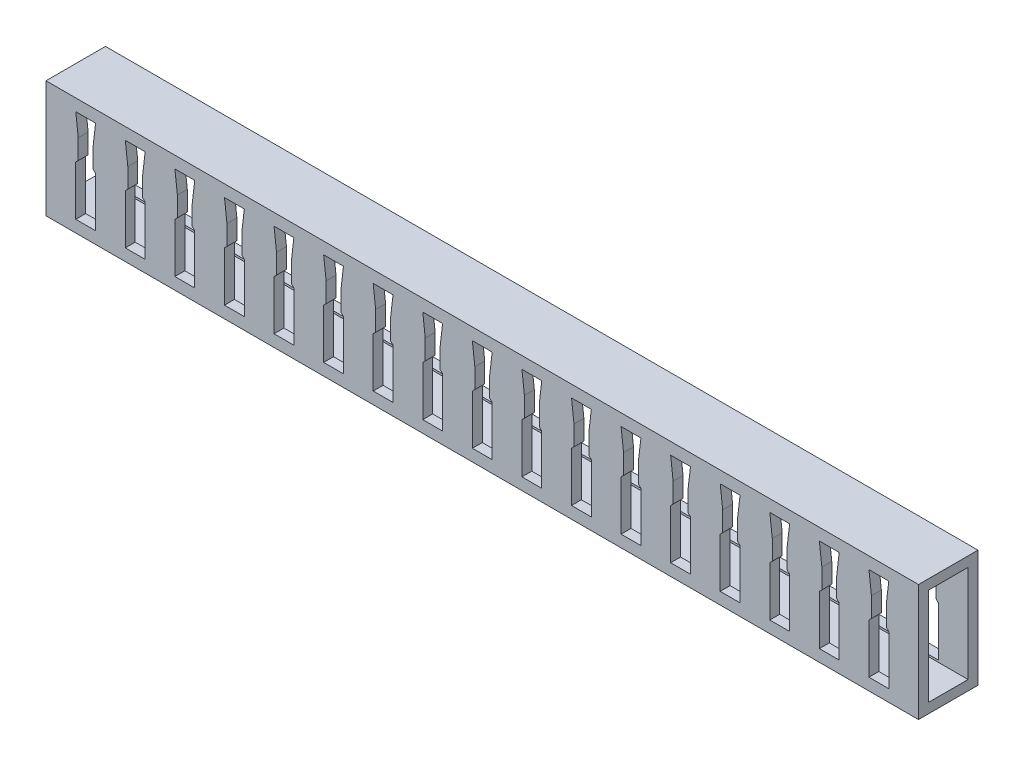
SolidWorks part; units mm, degrees
ref_plane "Front Plane" through (0, 0, 0) normal (0, 0, 1) x (1, 0, 0)
ref_plane "Top Plane" through (0, 0, 0) normal (0, 1, 0) x (1, 0, 0)
ref_plane "Right Plane" through (0, 0, 0) normal (1, 0, 0) x (0, 0, -1)
sketch "Sketch2" plane through (0, 0, 0) normal (1, 0, 0) x (0, 0, -1)
  line L1 (0, 0) -> (15.24, 0)
  line L2 (0, 0) -> (0, 29.972)
  line L3 (0, 29.972) -> (15.24, 29.972)
  line L4 (15.24, 0) -> (15.24, 29.972)
  dimension "D1" = 15.24
  dimension "D2" = 29.972
extrude "Boss-Extrude1" add sketch "Sketch2" along normal blind 223.52
sketch "Sketch3" plane through (223.52, 0, 0) normal (1, 0, 0) x (0, 0, -1)
  line L8 (2.54, 27.432) -> (2.54, 2.54)
  line L9 (2.54, 2.54) -> (12.7, 2.54)
  line L10 (12.7, 2.54) -> (12.7, 27.432)
  line L11 (12.7, 27.432) -> (2.54, 27.432)
  line L12 (2.54, 27.432) -> (2.54, 2.54)
  line L13 (2.54, 2.54) -> (12.7, 2.54)
  line L14 (12.7, 2.54) -> (12.7, 27.432)
  line L15 (12.7, 27.432) -> (2.54, 27.432)
  dimension "D1" = 2.54
extrude "Cut-Extrude1" cut sketch "Sketch3" against normal blind 419.1
sketch "Sketch4" plane through (0, 0, 0) normal (0, 0, 1) x (1, 0, 0)
  line L0 (7.62, 3.048) -> (7.62, 15.748)
  line L1 (7.62, 15.748) -> (8.255, 16.383)
  line L2 (8.255, 16.383) -> (8.255, 21.463)
  line L3 (8.255, 21.463) -> (7.62, 26.924)
  line L4 (7.62, 26.924) -> (12.7, 26.924)
  line L5 (12.7, 26.924) -> (12.065, 21.463)
  line L6 (12.065, 21.463) -> (12.065, 16.383)
  line L7 (12.065, 16.383) -> (12.7, 15.748)
  line L8 (12.7, 15.748) -> (12.7, 3.048)
  line L9 (12.7, 3.048) -> (7.62, 3.048)
  line L10 (223.52, 29.972) -> (0, 29.972) construction
  line L11 (223.52, 0) -> (0, 0) construction
  line L12 (0, 29.972) -> (0, 0) construction
  line L13 (25.4, 3.048) -> (20.32, 3.048)
  line L14 (20.32, 3.048) -> (20.32, 15.748)
  line L15 (20.32, 15.748) -> (20.955, 16.383)
  line L16 (20.955, 16.383) -> (20.955, 21.463)
  line L17 (20.955, 21.463) -> (20.32, 26.924)
  line L18 (20.32, 26.924) -> (25.4, 26.924)
  line L19 (25.4, 26.924) -> (24.765, 21.463)
  line L20 (24.765, 21.463) -> (24.765, 16.383)
  line L21 (24.765, 16.383) -> (25.4, 15.748)
  line L22 (25.4, 15.748) -> (25.4, 3.048)
  line L23 (38.1, 3.048) -> (33.02, 3.048)
  line L24 (33.02, 3.048) -> (33.02, 15.748)
  line L25 (33.02, 15.748) -> (33.655, 16.383)
  line L26 (33.655, 16.383) -> (33.655, 21.463)
  line L27 (33.655, 21.463) -> (33.02, 26.924)
  line L28 (33.02, 26.924) -> (38.1, 26.924)
  line L29 (38.1, 26.924) -> (37.465, 21.463)
  line L30 (37.465, 21.463) -> (37.465, 16.383)
  line L31 (37.465, 16.383) -> (38.1, 15.748)
  line L32 (38.1, 15.748) -> (38.1, 3.048)
  line L33 (50.8, 3.048) -> (45.72, 3.048)
  line L34 (45.72, 3.048) -> (45.72, 15.748)
  line L35 (45.72, 15.748) -> (46.355, 16.383)
  line L36 (46.355, 16.383) -> (46.355, 21.463)
  line L37 (46.355, 21.463) -> (45.72, 26.924)
  line L38 (45.72, 26.924) -> (50.8, 26.924)
  line L39 (50.8, 26.924) -> (50.165, 21.463)
  line L40 (50.165, 21.463) -> (50.165, 16.383)
  line L41 (50.165, 16.383) -> (50.8, 15.748)
  line L42 (50.8, 15.748) -> (50.8, 3.048)
  line L43 (63.5, 3.048) -> (58.42, 3.048)
  line L44 (58.42, 3.048) -> (58.42, 15.748)
  line L45 (58.42, 15.748) -> (59.055, 16.383)
  line L46 (59.055, 16.383) -> (59.055, 21.463)
  line L47 (59.055, 21.463) -> (58.42, 26.924)
  line L48 (58.42, 26.924) -> (63.5, 26.924)
  line L49 (63.5, 26.924) -> (62.865, 21.463)
  line L50 (62.865, 21.463) -> (62.865, 16.383)
  line L51 (62.865, 16.383) -> (63.5, 15.748)
  line L52 (63.5, 15.748) -> (63.5, 3.048)
  line L53 (76.2, 3.048) -> (71.12, 3.048)
  line L54 (71.12, 3.048) -> (71.12, 15.748)
  line L55 (71.12, 15.748) -> (71.755, 16.383)
  line L56 (71.755, 16.383) -> (71.755, 21.463)
  line L57 (71.755, 21.463) -> (71.12, 26.924)
  line L58 (71.12, 26.924) -> (76.2, 26.924)
  line L59 (76.2, 26.924) -> (75.565, 21.463)
  line L60 (75.565, 21.463) -> (75.565, 16.383)
  line L61 (75.565, 16.383) -> (76.2, 15.748)
  line L62 (76.2, 15.748) -> (76.2, 3.048)
  line L63 (88.9, 3.048) -> (83.82, 3.048)
  line L64 (83.82, 3.048) -> (83.82, 15.748)
  line L65 (83.82, 15.748) -> (84.455, 16.383)
  line L66 (84.455, 16.383) -> (84.455, 21.463)
  line L67 (84.455, 21.463) -> (83.82, 26.924)
  line L68 (83.82, 26.924) -> (88.9, 26.924)
  line L69 (88.9, 26.924) -> (88.265, 21.463)
  line L70 (88.265, 21.463) -> (88.265, 16.383)
  line L71 (88.265, 16.383) -> (88.9, 15.748)
  line L72 (88.9, 15.748) -> (88.9, 3.048)
  line L73 (101.6, 3.048) -> (96.52, 3.048)
  line L74 (96.52, 3.048) -> (96.52, 15.748)
  line L75 (96.52, 15.748) -> (97.155, 16.383)
  line L76 (97.155, 16.383) -> (97.155, 21.463)
  line L77 (97.155, 21.463) -> (96.52, 26.924)
  line L78 (96.52, 26.924) -> (101.6, 26.924)
  line L79 (101.6, 26.924) -> (100.965, 21.463)
  line L80 (100.965, 21.463) -> (100.965, 16.383)
  line L81 (100.965, 16.383) -> (101.6, 15.748)
  line L82 (101.6, 15.748) -> (101.6, 3.048)
  line L83 (114.3, 3.048) -> (109.22, 3.048)
  line L84 (109.22, 3.048) -> (109.22, 15.748)
  line L85 (109.22, 15.748) -> (109.855, 16.383)
  line L86 (109.855, 16.383) -> (109.855, 21.463)
  line L87 (109.855, 21.463) -> (109.22, 26.924)
  line L88 (109.22, 26.924) -> (114.3, 26.924)
  line L89 (114.3, 26.924) -> (113.665, 21.463)
  line L90 (113.665, 21.463) -> (113.665, 16.383)
  line L91 (113.665, 16.383) -> (114.3, 15.748)
  line L92 (114.3, 15.748) -> (114.3, 3.048)
  line L93 (127, 3.048) -> (121.92, 3.048)
  line L94 (121.92, 3.048) -> (121.92, 15.748)
  line L95 (121.92, 15.748) -> (122.555, 16.383)
  line L96 (122.555, 16.383) -> (122.555, 21.463)
  line L97 (122.555, 21.463) -> (121.92, 26.924)
  line L98 (121.92, 26.924) -> (127, 26.924)
  line L99 (127, 26.924) -> (126.365, 21.463)
  line L100 (126.365, 21.463) -> (126.365, 16.383)
  line L101 (126.365, 16.383) -> (127, 15.748)
  line L102 (127, 15.748) -> (127, 3.048)
  line L103 (139.7, 3.048) -> (134.62, 3.048)
  line L104 (134.62, 3.048) -> (134.62, 15.748)
  line L105 (134.62, 15.748) -> (135.255, 16.383)
  line L106 (135.255, 16.383) -> (135.255, 21.463)
  line L107 (135.255, 21.463) -> (134.62, 26.924)
  line L108 (134.62, 26.924) -> (139.7, 26.924)
  line L109 (139.7, 26.924) -> (139.065, 21.463)
  line L110 (139.065, 21.463) -> (139.065, 16.383)
  line L111 (139.065, 16.383) -> (139.7, 15.748)
  line L112 (139.7, 15.748) -> (139.7, 3.048)
  line L113 (152.4, 3.048) -> (147.32, 3.048)
  line L114 (147.32, 3.048) -> (147.32, 15.748)
  line L115 (147.32, 15.748) -> (147.955, 16.383)
  line L116 (147.955, 16.383) -> (147.955, 21.463)
  line L117 (147.955, 21.463) -> (147.32, 26.924)
  line L118 (147.32, 26.924) -> (152.4, 26.924)
  line L119 (152.4, 26.924) -> (151.765, 21.463)
  line L120 (151.765, 21.463) -> (151.765, 16.383)
  line L121 (151.765, 16.383) -> (152.4, 15.748)
  line L122 (152.4, 15.748) -> (152.4, 3.048)
  line L123 (165.1, 3.048) -> (160.02, 3.048)
  line L124 (160.02, 3.048) -> (160.02, 15.748)
  line L125 (160.02, 15.748) -> (160.655, 16.383)
  line L126 (160.655, 16.383) -> (160.655, 21.463)
  line L127 (160.655, 21.463) -> (160.02, 26.924)
  line L128 (160.02, 26.924) -> (165.1, 26.924)
  line L129 (165.1, 26.924) -> (164.465, 21.463)
  line L130 (164.465, 21.463) -> (164.465, 16.383)
  line L131 (164.465, 16.383) -> (165.1, 15.748)
  line L132 (165.1, 15.748) -> (165.1, 3.048)
  line L133 (177.8, 3.048) -> (172.72, 3.048)
  line L134 (172.72, 3.048) -> (172.72, 15.748)
  line L135 (172.72, 15.748) -> (173.355, 16.383)
  line L136 (173.355, 16.383) -> (173.355, 21.463)
  line L137 (173.355, 21.463) -> (172.72, 26.924)
  line L138 (172.72, 26.924) -> (177.8, 26.924)
  line L139 (177.8, 26.924) -> (177.165, 21.463)
  line L140 (177.165, 21.463) -> (177.165, 16.383)
  line L141 (177.165, 16.383) -> (177.8, 15.748)
  line L142 (177.8, 15.748) -> (177.8, 3.048)
  line L143 (190.5, 3.048) -> (185.42, 3.048)
  line L144 (185.42, 3.048) -> (185.42, 15.748)
  line L145 (185.42, 15.748) -> (186.055, 16.383)
  line L146 (186.055, 16.383) -> (186.055, 21.463)
  line L147 (186.055, 21.463) -> (185.42, 26.924)
  line L148 (185.42, 26.924) -> (190.5, 26.924)
  line L149 (190.5, 26.924) -> (189.865, 21.463)
  line L150 (189.865, 21.463) -> (189.865, 16.383)
  line L151 (189.865, 16.383) -> (190.5, 15.748)
  line L152 (190.5, 15.748) -> (190.5, 3.048)
  line L153 (203.2, 3.048) -> (198.12, 3.048)
  line L154 (198.12, 3.048) -> (198.12, 15.748)
  line L155 (198.12, 15.748) -> (198.755, 16.383)
  line L156 (198.755, 16.383) -> (198.755, 21.463)
  line L157 (198.755, 21.463) -> (198.12, 26.924)
  line L158 (198.12, 26.924) -> (203.2, 26.924)
  line L159 (203.2, 26.924) -> (202.565, 21.463)
  line L160 (202.565, 21.463) -> (202.565, 16.383)
  line L161 (202.565, 16.383) -> (203.2, 15.748)
  line L162 (203.2, 15.748) -> (203.2, 3.048)
  line L163 (215.9, 3.048) -> (210.82, 3.048)
  line L164 (210.82, 3.048) -> (210.82, 15.748)
  line L165 (210.82, 15.748) -> (211.455, 16.383)
  line L166 (211.455, 16.383) -> (211.455, 21.463)
  line L167 (211.455, 21.463) -> (210.82, 26.924)
  line L168 (210.82, 26.924) -> (215.9, 26.924)
  line L169 (215.9, 26.924) -> (215.265, 21.463)
  line L170 (215.265, 21.463) -> (215.265, 16.383)
  line L171 (215.265, 16.383) -> (215.9, 15.748)
  line L172 (215.9, 15.748) -> (215.9, 3.048)
  line L173 (228.6, 3.048) -> (223.52, 3.048)
  line L174 (223.52, 3.048) -> (223.52, 15.748)
  line L175 (223.52, 15.748) -> (224.155, 16.383)
  line L176 (224.155, 16.383) -> (224.155, 21.463)
  line L177 (224.155, 21.463) -> (223.52, 26.924)
  line L178 (223.52, 26.924) -> (228.6, 26.924)
  line L179 (228.6, 26.924) -> (227.965, 21.463)
  line L180 (227.965, 21.463) -> (227.965, 16.383)
  line L181 (227.965, 16.383) -> (228.6, 15.748)
  line L182 (228.6, 15.748) -> (228.6, 3.048)
  line L183 (241.3, 3.048) -> (236.22, 3.048)
  line L184 (236.22, 3.048) -> (236.22, 15.748)
  line L185 (236.22, 15.748) -> (236.855, 16.383)
  line L186 (236.855, 16.383) -> (236.855, 21.463)
  line L187 (236.855, 21.463) -> (236.22, 26.924)
  line L188 (236.22, 26.924) -> (241.3, 26.924)
  line L189 (241.3, 26.924) -> (240.665, 21.463)
  line L190 (240.665, 21.463) -> (240.665, 16.383)
  line L191 (240.665, 16.383) -> (241.3, 15.748)
  line L192 (241.3, 15.748) -> (241.3, 3.048)
  line L193 (254, 3.048) -> (248.92, 3.048)
  line L194 (248.92, 3.048) -> (248.92, 15.748)
  line L195 (248.92, 15.748) -> (249.555, 16.383)
  line L196 (249.555, 16.383) -> (249.555, 21.463)
  line L197 (249.555, 21.463) -> (248.92, 26.924)
  line L198 (248.92, 26.924) -> (254, 26.924)
  line L199 (254, 26.924) -> (253.365, 21.463)
  line L200 (253.365, 21.463) -> (253.365, 16.383)
  line L201 (253.365, 16.383) -> (254, 15.748)
  line L202 (254, 15.748) -> (254, 3.048)
  line L203 (266.7, 3.048) -> (261.62, 3.048)
  line L204 (261.62, 3.048) -> (261.62, 15.748)
  line L205 (261.62, 15.748) -> (262.255, 16.383)
  line L206 (262.255, 16.383) -> (262.255, 21.463)
  line L207 (262.255, 21.463) -> (261.62, 26.924)
  line L208 (261.62, 26.924) -> (266.7, 26.924)
  line L209 (266.7, 26.924) -> (266.065, 21.463)
  line L210 (266.065, 21.463) -> (266.065, 16.383)
  line L211 (266.065, 16.383) -> (266.7, 15.748)
  line L212 (266.7, 15.748) -> (266.7, 3.048)
  line L213 (279.4, 3.048) -> (274.32, 3.048)
  line L214 (274.32, 3.048) -> (274.32, 15.748)
  line L215 (274.32, 15.748) -> (274.955, 16.383)
  line L216 (274.955, 16.383) -> (274.955, 21.463)
  line L217 (274.955, 21.463) -> (274.32, 26.924)
  line L218 (274.32, 26.924) -> (279.4, 26.924)
  line L219 (279.4, 26.924) -> (278.765, 21.463)
  line L220 (278.765, 21.463) -> (278.765, 16.383)
  line L221 (278.765, 16.383) -> (279.4, 15.748)
  line L222 (279.4, 15.748) -> (279.4, 3.048)
  line L223 (292.1, 3.048) -> (287.02, 3.048)
  line L224 (287.02, 3.048) -> (287.02, 15.748)
  line L225 (287.02, 15.748) -> (287.655, 16.383)
  line L226 (287.655, 16.383) -> (287.655, 21.463)
  line L227 (287.655, 21.463) -> (287.02, 26.924)
  line L228 (287.02, 26.924) -> (292.1, 26.924)
  line L229 (292.1, 26.924) -> (291.465, 21.463)
  line L230 (291.465, 21.463) -> (291.465, 16.383)
  line L231 (291.465, 16.383) -> (292.1, 15.748)
  line L232 (292.1, 15.748) -> (292.1, 3.048)
  line L233 (304.8, 3.048) -> (299.72, 3.048)
  line L234 (299.72, 3.048) -> (299.72, 15.748)
  line L235 (299.72, 15.748) -> (300.355, 16.383)
  line L236 (300.355, 16.383) -> (300.355, 21.463)
  line L237 (300.355, 21.463) -> (299.72, 26.924)
  line L238 (299.72, 26.924) -> (304.8, 26.924)
  line L239 (304.8, 26.924) -> (304.165, 21.463)
  line L240 (304.165, 21.463) -> (304.165, 16.383)
  line L241 (304.165, 16.383) -> (304.8, 15.748)
  line L242 (304.8, 15.748) -> (304.8, 3.048)
  line L243 (317.5, 3.048) -> (312.42, 3.048)
  line L244 (312.42, 3.048) -> (312.42, 15.748)
  line L245 (312.42, 15.748) -> (313.055, 16.383)
  line L246 (313.055, 16.383) -> (313.055, 21.463)
  line L247 (313.055, 21.463) -> (312.42, 26.924)
  line L248 (312.42, 26.924) -> (317.5, 26.924)
  line L249 (317.5, 26.924) -> (316.865, 21.463)
  line L250 (316.865, 21.463) -> (316.865, 16.383)
  line L251 (316.865, 16.383) -> (317.5, 15.748)
  line L252 (317.5, 15.748) -> (317.5, 3.048)
  line L253 (330.2, 3.048) -> (325.12, 3.048)
  line L254 (325.12, 3.048) -> (325.12, 15.748)
  line L255 (325.12, 15.748) -> (325.755, 16.383)
  line L256 (325.755, 16.383) -> (325.755, 21.463)
  line L257 (325.755, 21.463) -> (325.12, 26.924)
  line L258 (325.12, 26.924) -> (330.2, 26.924)
  line L259 (330.2, 26.924) -> (329.565, 21.463)
  line L260 (329.565, 21.463) -> (329.565, 16.383)
  line L261 (329.565, 16.383) -> (330.2, 15.748)
  line L262 (330.2, 15.748) -> (330.2, 3.048)
  line L263 (342.9, 3.048) -> (337.82, 3.048)
  line L264 (337.82, 3.048) -> (337.82, 15.748)
  line L265 (337.82, 15.748) -> (338.455, 16.383)
  line L266 (338.455, 16.383) -> (338.455, 21.463)
  line L267 (338.455, 21.463) -> (337.82, 26.924)
  line L268 (337.82, 26.924) -> (342.9, 26.924)
  line L269 (342.9, 26.924) -> (342.265, 21.463)
  line L270 (342.265, 21.463) -> (342.265, 16.383)
  line L271 (342.265, 16.383) -> (342.9, 15.748)
  line L272 (342.9, 15.748) -> (342.9, 3.048)
  line L273 (355.6, 3.048) -> (350.52, 3.048)
  line L274 (350.52, 3.048) -> (350.52, 15.748)
  line L275 (350.52, 15.748) -> (351.155, 16.383)
  line L276 (351.155, 16.383) -> (351.155, 21.463)
  line L277 (351.155, 21.463) -> (350.52, 26.924)
  line L278 (350.52, 26.924) -> (355.6, 26.924)
  line L279 (355.6, 26.924) -> (354.965, 21.463)
  line L280 (354.965, 21.463) -> (354.965, 16.383)
  line L281 (354.965, 16.383) -> (355.6, 15.748)
  line L282 (355.6, 15.748) -> (355.6, 3.048)
  line L283 (368.3, 3.048) -> (363.22, 3.048)
  line L284 (363.22, 3.048) -> (363.22, 15.748)
  line L285 (363.22, 15.748) -> (363.855, 16.383)
  line L286 (363.855, 16.383) -> (363.855, 21.463)
  line L287 (363.855, 21.463) -> (363.22, 26.924)
  line L288 (363.22, 26.924) -> (368.3, 26.924)
  line L289 (368.3, 26.924) -> (367.665, 21.463)
  line L290 (367.665, 21.463) -> (367.665, 16.383)
  line L291 (367.665, 16.383) -> (368.3, 15.748)
  line L292 (368.3, 15.748) -> (368.3, 3.048)
  line L293 (381, 3.048) -> (375.92, 3.048)
  line L294 (375.92, 3.048) -> (375.92, 15.748)
  line L295 (375.92, 15.748) -> (376.555, 16.383)
  line L296 (376.555, 16.383) -> (376.555, 21.463)
  line L297 (376.555, 21.463) -> (375.92, 26.924)
  line L298 (375.92, 26.924) -> (381, 26.924)
  line L299 (381, 26.924) -> (380.365, 21.463)
  line L300 (380.365, 21.463) -> (380.365, 16.383)
  line L301 (380.365, 16.383) -> (381, 15.748)
  line L302 (381, 15.748) -> (381, 3.048)
  line L303 (393.7, 3.048) -> (388.62, 3.048)
  line L304 (388.62, 3.048) -> (388.62, 15.748)
  line L305 (388.62, 15.748) -> (389.255, 16.383)
  line L306 (389.255, 16.383) -> (389.255, 21.463)
  line L307 (389.255, 21.463) -> (388.62, 26.924)
  line L308 (388.62, 26.924) -> (393.7, 26.924)
  line L309 (393.7, 26.924) -> (393.065, 21.463)
  line L310 (393.065, 21.463) -> (393.065, 16.383)
  line L311 (393.065, 16.383) -> (393.7, 15.748)
  line L312 (393.7, 15.748) -> (393.7, 3.048)
  line L313 (406.4, 3.048) -> (401.32, 3.048)
  line L314 (401.32, 3.048) -> (401.32, 15.748)
  line L315 (401.32, 15.748) -> (401.955, 16.383)
  line L316 (401.955, 16.383) -> (401.955, 21.463)
  line L317 (401.955, 21.463) -> (401.32, 26.924)
  line L318 (401.32, 26.924) -> (406.4, 26.924)
  line L319 (406.4, 26.924) -> (405.765, 21.463)
  line L320 (405.765, 21.463) -> (405.765, 16.383)
  line L321 (405.765, 16.383) -> (406.4, 15.748)
  line L322 (406.4, 15.748) -> (406.4, 3.048)
  dimension "D1" = 3.048
  dimension "D2" = 3.048
  dimension "D3" = 5.08
  dimension "D4" = 3.81
  dimension "D5" = 5.08
  dimension "D6" = 12.7
  dimension "D7" = 5.08
  dimension "D8" = 7.62
  dimension "D10" = 8.89
  dimension "D9" = 32
extrude "Cut-Extrude2" cut sketch "Sketch4" against normal blind 419.1
